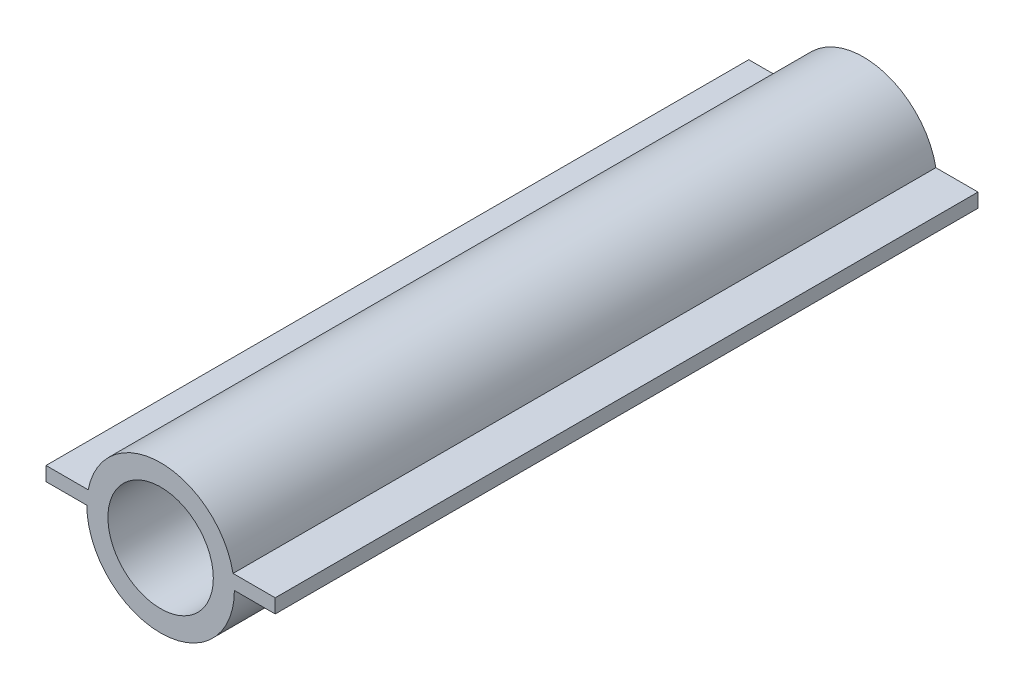
SolidWorks part; units mm, degrees
ref_plane "Front Plane" through (0, 0, 0) normal (0, 0, 1) x (1, 0, 0)
ref_plane "Top Plane" through (0, 0, 0) normal (0, 1, 0) x (1, 0, 0)
ref_plane "Right Plane" through (0, 0, 0) normal (1, 0, 0) x (0, 0, -1)
sketch "Sketch2" plane through (0, 0, 0) normal (0, 0, 1) x (1, 0, 0)
  line L1 (-8.1539, 0) -> (-5.25, 0)
  line L2 (-8.1539, 1) -> (-8.1539, 0)
  line L3 (5.1539, 1) -> (8.1539, 1)
  line L4 (8.1539, 1) -> (8.1539, 0)
  line L5 (8.1539, 0) -> (5.25, 0)
  line L6 (-5.1539, 1) -> (-8.1539, 1)
  circle A0 centre (0, 0) radius 3.75
  arc A1 (5.1539, 1) -> (-5.1539, 1) centre (0, 0) ccw
  arc A2 (-5.25, 0) -> (5.25, 0) centre (0, 0) ccw
  dimension "D1" = 7.5
  dimension "D2" = 10.5
  dimension "D3" = 1
  dimension "D4" = 3
extrude "Boss-Extrude1" add sketch "Sketch2" along normal blind 50
